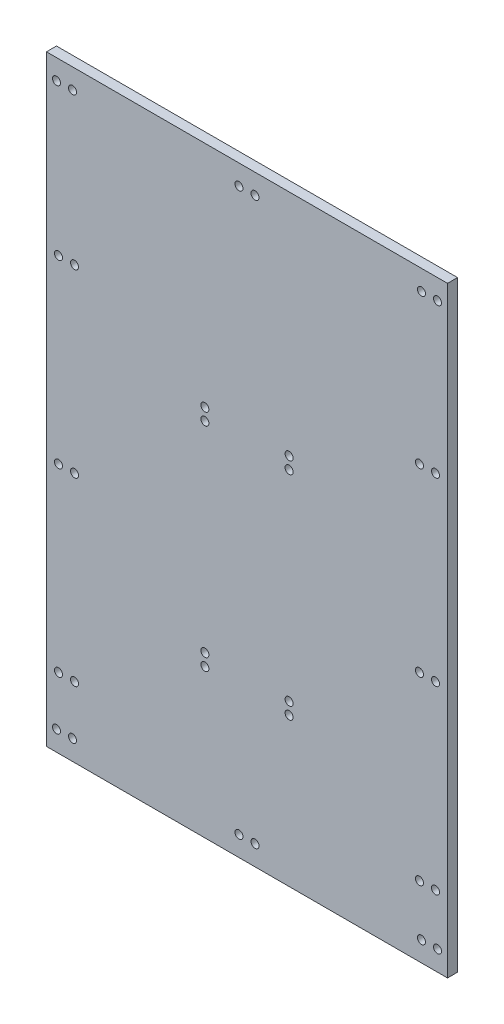
SolidWorks part; units mm, degrees
ref_plane "Front Plane" through (0, 0, 0) normal (0, 0, 1) x (1, 0, 0)
ref_plane "Top Plane" through (0, 0, 0) normal (0, 1, 0) x (1, 0, 0)
ref_plane "Right Plane" through (0, 0, 0) normal (1, 0, 0) x (0, 0, -1)
sketch "Sketch1" plane through (0, 0, 0) normal (0, 0, 1) x (1, 0, 0)
  line L1 (-100, -150) -> (100, -150)
  line L2 (-100, -150) -> (-100, 150)
  line L3 (-100, 150) -> (100, 150)
  line L4 (100, -150) -> (100, 150)
  line L5 (-100, -150) -> (100, 150) construction
  line L6 (-100, 150) -> (100, -150) construction
  point P0 (0, 0)
  dimension "D1" = 200
  dimension "D2" = 300
extrude "Boss-Extrude1" add sketch "Sketch1" along normal blind 5
sketch "Sketch2" plane through (0, 0, 5) normal (0, 0, 1) x (1, 0, 0)
  line L0 (-100, -25) -> (100, -25) construction
  line L1 (-100, 150) -> (-100, -150) construction
  line L2 (100, -150) -> (100, 150) construction
  line L3 (0, -0.7254) -> (0, -19.3655) construction
  line L4 (-100, 20) -> (100, 20) construction
  line L5 (0, 40.7254) -> (0, 59.3655) construction
  line L6 (-100, 65) -> (100, 65) construction
  line L7 (-100, -115) -> (100, -115) construction
  line L8 (0, -90.7254) -> (0, -109.3655) construction
  line L9 (-100, -150) -> (100, -150) construction
  circle A2 centre (-86, -25) radius 2
  circle A3 centre (-94, -25) radius 2
  circle A4 centre (86, -25) radius 2
  circle A5 centre (94, -25) radius 2
  circle A6 centre (94, 65) radius 2
  circle A7 centre (86, 65) radius 2
  circle A8 centre (-94, 65) radius 2
  circle A9 centre (-86, 65) radius 2
  circle A14 centre (-86, -115) radius 2
  circle A15 centre (-94, -115) radius 2
  circle A16 centre (86, -115) radius 2
  circle A17 centre (94, -115) radius 2
  dimension "D1" = 172
  dimension "D2" = 8
  dimension "D3" = 4
  dimension "D5" = 90
  dimension "D6" = 35
  dimension "D4" = 2
extrude "Cut-Extrude1" cut sketch "Sketch2" against normal blind 5
sketch "Sketch3" plane through (0, 0, 5) normal (0, 0, 1) x (1, 0, 0)
  line L0 (0, 24.2296) -> (0, -77.2221) construction
  line L1 (-31.5028, -20) -> (30.7981, -20) construction
  line L2 (-100, -150) -> (100, -150) construction
  circle A0 centre (-21, 30) radius 2
  circle A1 centre (-21, 36) radius 2
  circle A2 centre (21, 36) radius 2
  circle A3 centre (21, 30) radius 2
  circle A4 centre (21, -70) radius 2
  circle A5 centre (21, -76) radius 2
  circle A6 centre (-21, -76) radius 2
  circle A7 centre (-21, -70) radius 2
  dimension "D1" = 4
  dimension "D2" = 6
  dimension "D3" = 42
  dimension "D4" = 100
  dimension "D5" = 130
extrude "Cut-Extrude2" cut sketch "Sketch3" against normal blind 5
sketch "Sketch4" plane through (0, 0, 5) normal (0, 0, 1) x (1, 0, 0)
  line L0 (-100, 0) -> (100, 0) construction
  line L1 (-100, 150) -> (-100, -150) construction
  line L2 (100, -150) -> (100, 150) construction
  line L3 (-100, 140) -> (100, 140) construction
  line L4 (0, 150) -> (0, -150) construction
  line L5 (-100, -150) -> (100, -150) construction
  line L6 (100, 150) -> (-100, 150) construction
  line L7 (-100, -140) -> (100, -140) construction
  circle A1 centre (-95, 140) radius 2
  circle A2 centre (-87, 140) radius 2
  circle A3 centre (-4, 140) radius 2
  circle A4 centre (4, 140) radius 2
  circle A5 centre (95, 140) radius 2
  circle A6 centre (87, 140) radius 2
  circle A7 centre (87, -140) radius 2
  circle A8 centre (95, -140) radius 2
  circle A9 centre (4, -140) radius 2
  circle A10 centre (-4, -140) radius 2
  circle A11 centre (-87, -140) radius 2
  circle A12 centre (-95, -140) radius 2
  dimension "D1" = 4
  dimension "D2" = 8
  dimension "D3" = 5
  dimension "D4" = 8
  dimension "D5" = 4
  dimension "D6" = 10
extrude "Cut-Extrude3" cut sketch "Sketch4" against normal blind 214
